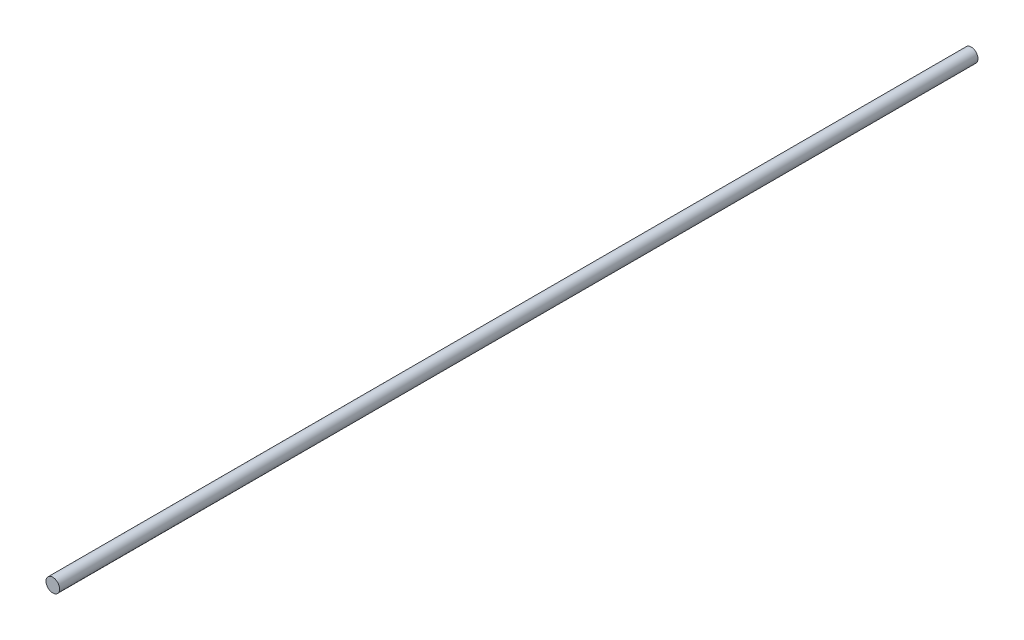
SolidWorks part; units mm, degrees
material "Hexcel AS4C (3000 Filaments)"
ref_plane "Front Plane" through (0, 0, 0) normal (0, 0, 1) x (1, 0, 0)
ref_plane "Top Plane" through (0, 0, 0) normal (0, 1, 0) x (1, 0, 0)
ref_plane "Right Plane" through (0, 0, 0) normal (1, 0, 0) x (0, 0, -1)
sketch "Sketch1" plane through (0, 0, 0) normal (0, 0, 1) x (1, 0, 0)
  circle A0 centre (0, 0) radius 1
  dimension "D1" = 2
extrude "Boss-Extrude1" add sketch "Sketch1" along normal blind 135
